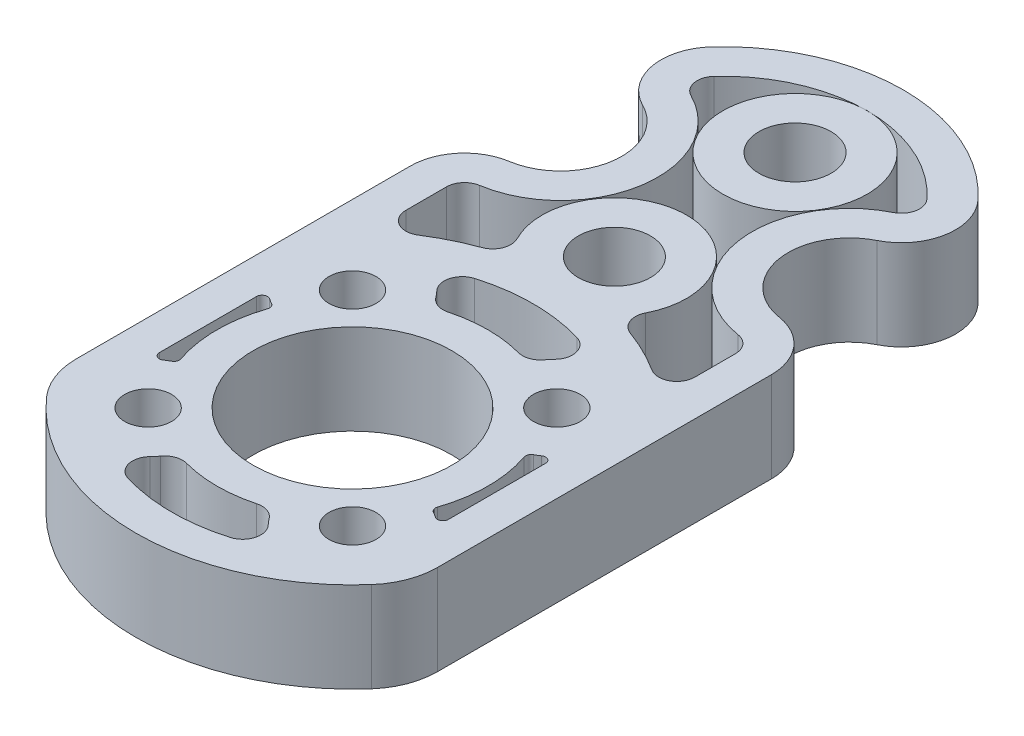
SolidWorks part; units mm, degrees
ref_plane "Front Plane" through (0, 0, 0) normal (0, 0, 1) x (1, 0, 0)
ref_plane "Top Plane" through (0, 0, 0) normal (0, 1, 0) x (1, 0, 0)
ref_plane "Right Plane" through (0, 0, 0) normal (1, 0, 0) x (0, 0, -1)
sketch "Sketch1" plane through (0, 0, 0) normal (0, 1, 0) x (1, 0, 0)
  line L0 (0, 0) -> (5.6569, 5.6569) construction
  line L1 (0, 0) -> (0, -11.5) construction
  line L2 (0, -11.5) -> (0, -7.5) construction
  line L3 (0, 12.5) -> (0, 16.5) construction
  line L4 (-10, 13.2012) -> (-10, -5.2915)
  line L5 (10, 13.2012) -> (10, -5.2915)
  line L7 (8, 13.2012) -> (8, 10.9545)
  line L8 (-8, 2.6928) -> (-8, -2.6928)
  line L10 (8, 2.6928) -> (8, -2.6928)
  line L12 (-8, 13.2012) -> (-8, 10.9545)
  circle A0 centre (0, 0) radius 5.5
  circle A1 centre (0, 14.5) radius 2
  circle A2 centre (5.6569, 5.6569) radius 1.5 construction
  circle A3 centre (0, 24.5) radius 2
  circle A4 centre (5.6569, -5.6569) radius 1.5 construction
  circle A5 centre (0, 24.5) radius 4
  arc A6 (-7.5297, 2.9398) -> (-7.244, 2.7636) centre (-5.6569, 5.6569) ccw
  arc A7 (7.3627, 27.2669) -> (-7.3627, 27.2669) centre (0, 20.5) ccw
  circle A8 centre (-5.6569, 5.6569) radius 1.5 construction
  arc A9 (1.9391, -7.245) -> (3.0021, -7.617) centre (2.1976, -8.211) cw
  arc A10 (8, 9.6047) -> (3.1896, 12.0862) centre (0, 0) ccw construction
  arc A11 (-8.8235, -8.8541) -> (8.8235, -8.8541) centre (0, 0) ccw construction
  arc A12 (3.5581, 12.6724) -> (-3.5581, 12.6724) centre (0, 14.5) ccw
  circle A13 centre (-5.6569, -5.6569) radius 3.3 construction
  arc A14 (5.8902, 25.9135) -> (-5.8902, 25.9135) centre (0, 20.5) ccw
  arc A15 (1.9391, 7.245) -> (-1.9391, 7.245) centre (0, 0) ccw
  arc A16 (2.8346, 9.5898) -> (-2.8346, 9.5898) centre (0, 0) ccw
  arc A17 (-3.2734, -7.9392) -> (-3.0021, -7.617) centre (-5.6569, -5.6569) ccw
  arc A18 (5.5992, 24.3414) -> (7.1565, 14.1889) centre (8, 19.514) ccw
  arc A19 (-3.0021, 7.617) -> (-3.2734, 7.9392) centre (-5.6569, 5.6569) ccw
  arc A20 (7.1041, -2.4044) -> (7.1041, 2.4044) centre (0, 0) ccw
  arc A21 (-3.1896, 12.0862) -> (-8, 9.6047) centre (0, 0) ccw construction
  arc A22 (2.8346, -9.5898) -> (3.2734, -7.9392) centre (2.5512, -8.6309) ccw
  arc A23 (10, -5.2915) -> (9, -7.9373) centre (6, -5.2915) cw
  arc A24 (3.2734, 7.9392) -> (3.0021, 7.617) centre (5.6569, 5.6569) ccw
  arc A25 (-1.9391, -7.245) -> (1.9391, -7.245) centre (0, 0) ccw
  arc A26 (-2.8346, -9.5898) -> (2.8346, -9.5898) centre (0, 0) ccw
  arc A27 (7.244, 2.7636) -> (7.5297, 2.9398) centre (5.6569, 5.6569) ccw
  arc A28 (8, 13.2012) -> (7.1565, 14.1889) centre (7, 13.2012) ccw
  arc A29 (-2.8346, -9.5898) -> (-3.2734, -7.9392) centre (-2.5512, -8.6309) cw
  arc A30 (5.5992, 24.3414) -> (5.8902, 25.9135) centre (5.1539, 25.2368) ccw
  arc A31 (-7.1041, 2.4044) -> (-7.1041, -2.4044) centre (0, 0) ccw
  arc A32 (-10, -5.2915) -> (-9, -7.9373) centre (-6, -5.2915) ccw
  arc A33 (10, 13.2012) -> (7.4694, 16.1642) centre (7, 13.2012) ccw
  arc A34 (6.4898, 22.5507) -> (7.4694, 16.1642) centre (8, 19.514) ccw
  arc A35 (6.4898, 22.5507) -> (7.3627, 27.2669) centre (5.1539, 25.2368) ccw
  arc A36 (-8, 13.2012) -> (-7.1565, 14.1889) centre (-7, 13.2012) cw
  arc A37 (-10, 13.2012) -> (-7.4694, 16.1642) centre (-7, 13.2012) cw
  arc A38 (-6.4898, 22.5507) -> (-7.4694, 16.1642) centre (-8, 19.514) cw
  arc A39 (-5.5992, 24.3414) -> (-7.1565, 14.1889) centre (-8, 19.514) cw
  arc A40 (-6.4898, 22.5507) -> (-7.3627, 27.2669) centre (-5.1539, 25.2368) cw
  arc A41 (-5.5992, 24.3414) -> (-5.8902, 25.9135) centre (-5.1539, 25.2368) cw
  arc A42 (3.062, 11.6028) -> (2.8206, 11.6638) centre (0, 0) ccw
  arc A43 (6.4615, 10.1118) -> (4.1055, 11.2759) centre (0, 0) ccw
  arc A44 (-9, -7.9373) -> (9, -7.9373) centre (0, 0) ccw
  arc A45 (-4.1055, 11.2759) -> (-6.4615, 10.1118) centre (0, 0) ccw
  arc A46 (-3.5581, 12.6724) -> (-4.1055, 11.2759) centre (-4.4476, 12.2155) cw
  arc A47 (-8, 10.9545) -> (-6.4615, 10.1118) centre (-7, 10.9545) ccw
  arc A48 (8, 10.9545) -> (6.4615, 10.1118) centre (7, 10.9545) cw
  arc A49 (3.5581, 12.6724) -> (4.1055, 11.2759) centre (4.4476, 12.2155) ccw
  arc A50 (-1.9391, -7.245) -> (-3.0021, -7.617) centre (-2.1976, -8.211) ccw
  arc A51 (3.0021, -7.617) -> (3.2734, -7.9392) centre (5.6569, -5.6569) ccw
  arc A52 (7.5297, -2.9398) -> (7.244, -2.7636) centre (5.6569, -5.6569) ccw
  arc A53 (-1.9391, 7.245) -> (-3.0021, 7.617) centre (-2.1976, 8.211) cw
  arc A54 (1.9391, 7.245) -> (3.0021, 7.617) centre (2.1976, 8.211) ccw
  arc A55 (2.8346, 9.5898) -> (3.2734, 7.9392) centre (2.5512, 8.6309) cw
  arc A56 (-2.8346, 9.5898) -> (-3.2734, 7.9392) centre (-2.5512, 8.6309) ccw
  arc A57 (7.1041, 2.4044) -> (7.244, 2.7636) centre (7.3883, 2.5006) cw
  arc A58 (8, 2.6928) -> (7.5297, 2.9398) centre (7.7, 2.6928) ccw
  arc A59 (8, -2.6928) -> (7.5297, -2.9398) centre (7.7, -2.6928) cw
  arc A60 (7.1041, -2.4044) -> (7.244, -2.7636) centre (7.3883, -2.5006) ccw
  arc A61 (-8, -2.6928) -> (-7.5297, -2.9398) centre (-7.7, -2.6928) ccw
  arc A62 (-7.1041, -2.4044) -> (-7.244, -2.7636) centre (-7.3883, -2.5006) cw
  arc A63 (-7.1041, 2.4044) -> (-7.244, 2.7636) centre (-7.3883, 2.5006) ccw
  arc A64 (-8, 2.6928) -> (-7.5297, 2.9398) centre (-7.7, 2.6928) cw
  circle A66 centre (5.6569, -5.6569) radius 1.3
  circle A67 centre (-5.6569, -5.6569) radius 1.3
  circle A68 centre (-5.6569, 5.6569) radius 1.3
  circle A69 centre (5.6569, 5.6569) radius 1.3
  arc A73 (-7.244, -2.7636) -> (-7.5297, -2.9398) centre (-5.6569, -5.6569) ccw
  point P24 (0, 0)
  point P32 (0, 0)
  point P97 (-2.8206, 11.6638)
  point P109 (-2.6499, -7.0163)
  point P120 (-2.4613, 7.0846)
  point P134 (0, 0)
  dimension "D1" = 4
  dimension "D2" = 1
  dimension "D3" = 1
  dimension "D4" = 1
  dimension "D5" = 0.3
  dimension "D7" = 0.2
  dimension "D8" = 2
extrude "Boss-Extrude1" add sketch "Sketch1" along normal blind 5
